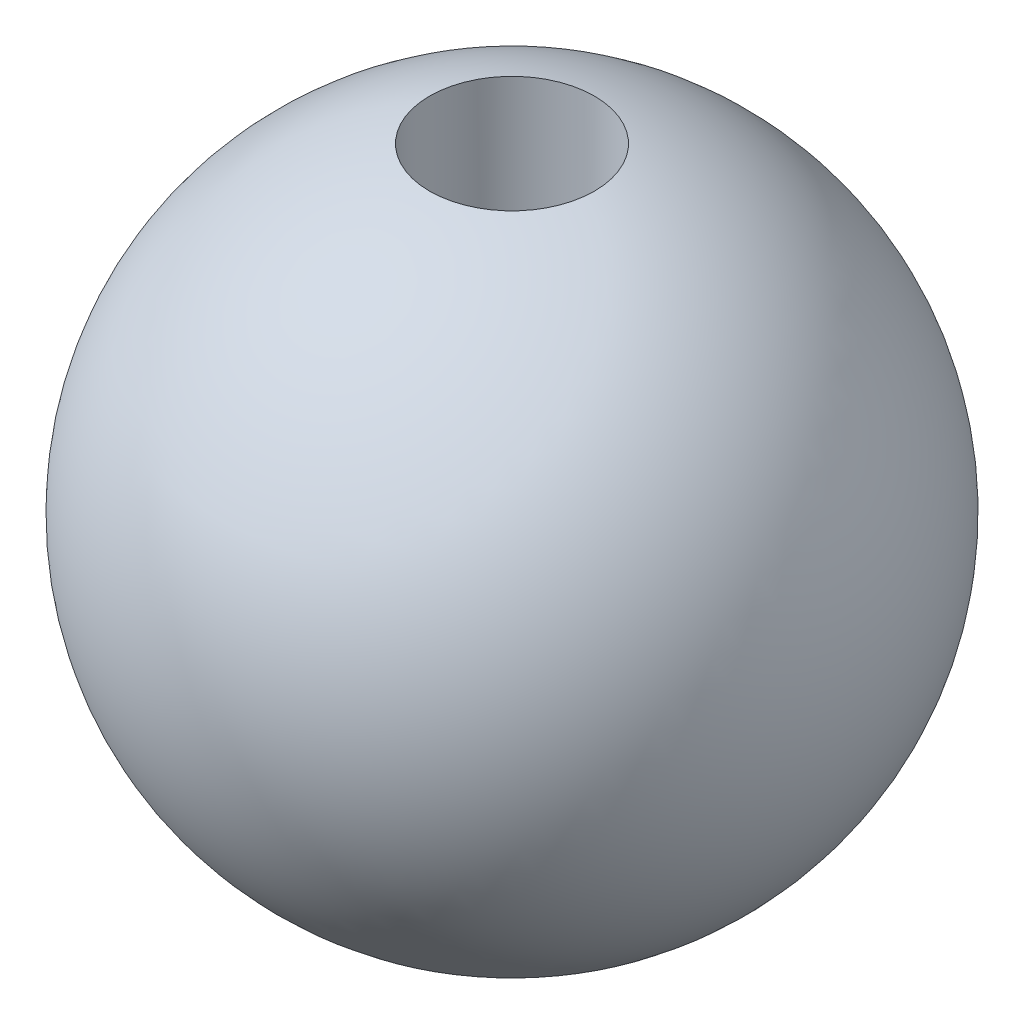
SolidWorks part; units mm, degrees
ref_plane "Front Plane" through (0, 0, 0) normal (0, 0, 1) x (1, 0, 0)
ref_plane "Top Plane" through (0, 0, 0) normal (0, 1, 0) x (1, 0, 0)
ref_plane "Right Plane" through (0, 0, 0) normal (1, 0, 0) x (0, 0, -1)
sketch "Sketch1" plane through (0, 0, 0) normal (0, 0, 1) x (1, 0, 0)
  line L0 (0, 10) -> (0, -10)
  arc A0 (0, 10) -> (0, -10) centre (0, 0) ccw
  dimension "D1" = 20
revolve "Revolve1" add sketch "Sketch1" angle 360 about L0
ref_plane "Plane1" through (0, 10, 0) normal (0, 1, 0) x (1, 0, 0)
sketch "Sketch2" plane through (0, 10, 0) normal (0, 1, 0) x (1, 0, 0)
  point P0 (0, 0)
hole_wizard "M6 Tapped Hole1" positions "Sketch3" profile "Sketch4" tap size "M6" standard "ISO"
sketch "Sketch3" plane through (0, 10, 0) normal (0, 1, 0) x (1, 0, 0)
  point P0 (0, 0)
sketch "Sketch4" plane through (0, 10, 0) normal (1, 0, 0) x (0, 0, 1)
  line L0 (0, 0) -> (0, 6)
  line L1 (0, 6) -> (2.5, 6)
  line L2 (2.5, 6) -> (2.5, 0)
  line L5 (2.5, 0) -> (0, 0)
  line L10 (0, 6) -> (-2.5, 6) construction
  line L11 (0, -6.35) -> (0, 107.95) construction
  dimension "Tap Drill Dia." = 5
  dimension "Tap Drill Depth" = 6
  dimension "Drill Angle" = 180
cosmetic thread "Hole Thread1" parameters "D1"=6, "D2"=6
sketch "Sketch5" plane through (0, 0, 0) normal (0, 0, 1) x (1, 0, 0)
  line L0 (0, -10) -> (0, -2)
  line L1 (0, -2) -> (9.798, -2)
  arc A0 (-2.5, 9.6825) -> (2.5, 9.6825) centre (0, 0) ccw construction
  dimension "D1" = 9.798
  dimension "D2" = 8
